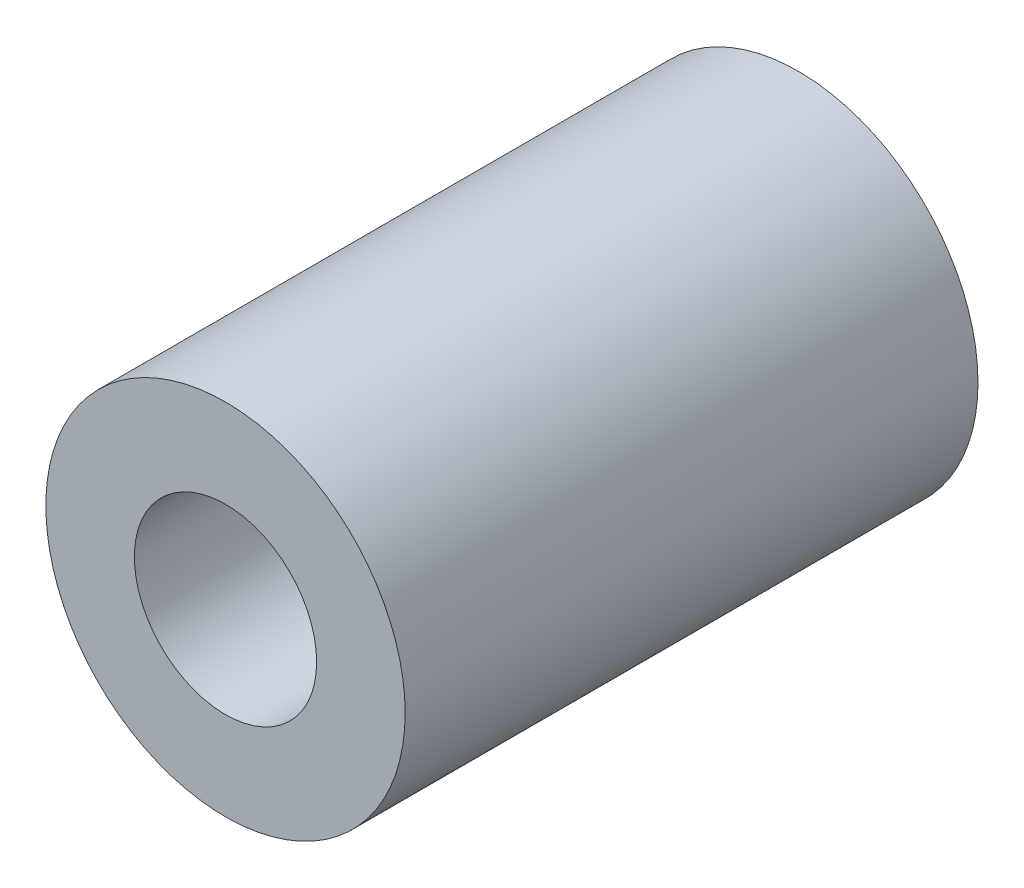
SolidWorks part; units mm, degrees
ref_plane "正面" through (0, 0, 0) normal (0, 0, 1) x (1, 0, 0)
ref_plane "平面" through (0, 0, 0) normal (0, 1, 0) x (1, 0, 0)
ref_plane "右側面" through (0, 0, 0) normal (1, 0, 0) x (0, 0, -1)
sketch "ｽｹｯﾁ1" plane through (0, 0, 0) normal (0, 0, 1) x (1, 0, 0)
  circle A0 centre (0, 0) radius 1.75
  circle A1 centre (0, 0) radius 3.45
  dimension "D1" = 3.5
  dimension "D2" = 6.9
extrude "ﾎﾞｽ - 押し出し1" add sketch "ｽｹｯﾁ1" along normal blind 11
